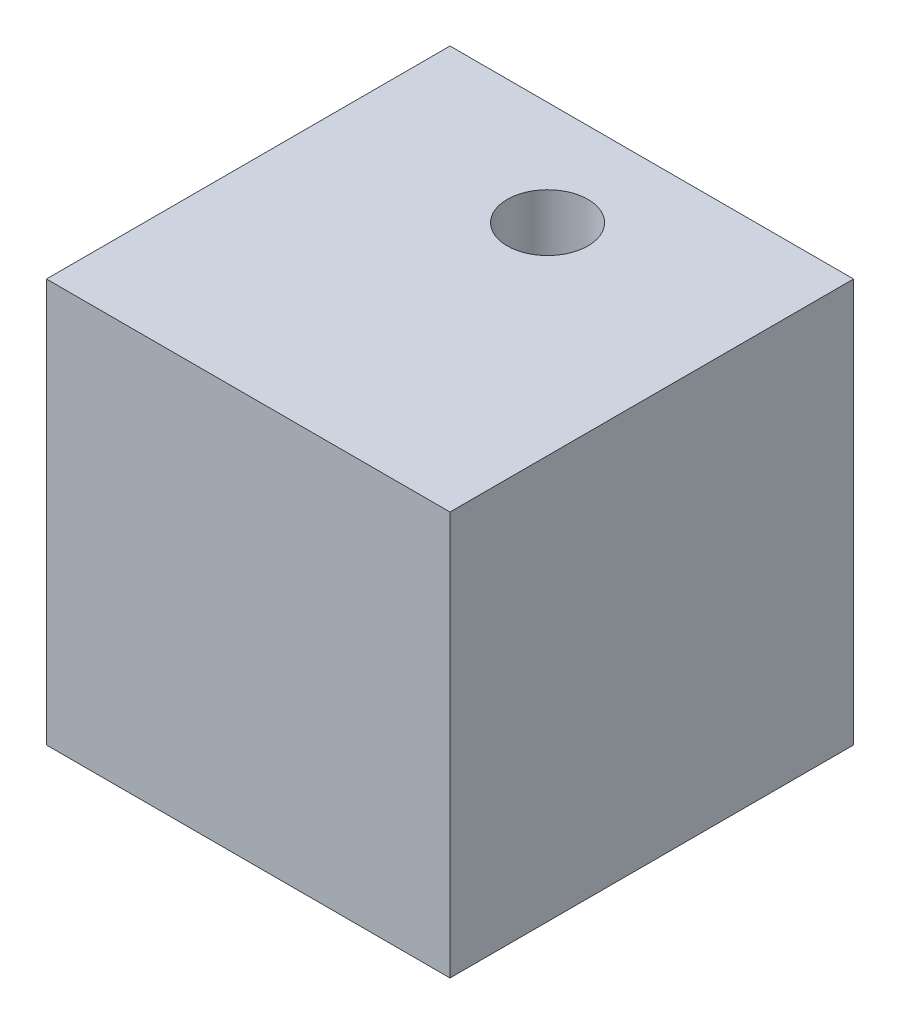
SolidWorks part; units mm, degrees
ref_plane "前视基准面" through (0, 0, 0) normal (0, 0, 1) x (1, 0, 0)
ref_plane "上视基准面" through (0, 0, 0) normal (0, 1, 0) x (1, 0, 0)
ref_plane "右视基准面" through (0, 0, 0) normal (1, 0, 0) x (0, 0, -1)
sketch "草图1" plane through (0, 0, 0) normal (0, 1, 0) x (1, 0, 0)
  line L1 (-15, 15) -> (15, 15)
  line L2 (-15, 15) -> (-15, -15)
  line L3 (-15, -15) -> (15, -15)
  line L4 (15, 15) -> (15, -15)
  line L5 (-15, 15) -> (15, -15) construction
  line L6 (-15, -15) -> (15, 15) construction
  point P0 (0, 0)
  dimension "D1" = 30
  dimension "D2" = 30
extrude "凸台-拉伸1" add sketch "草图1" along normal blind 30
sketch "草图2" plane through (0, 30, 0) normal (0, 1, 0) x (1, 0, 0)
  circle A0 centre (0, 7.2545) radius 3
  dimension "D1" = 6
extrude "切除-拉伸1" cut sketch "草图2" against normal blind 10 contours A0
